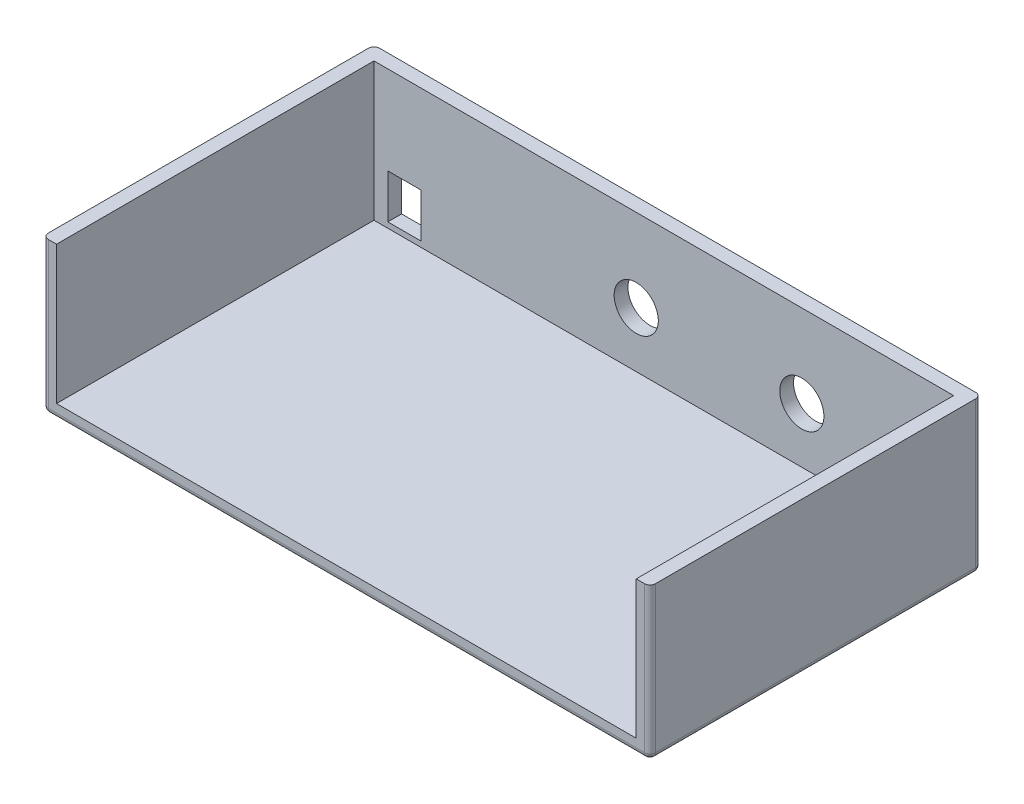
SolidWorks part; units mm, degrees
ref_plane "Alzado" through (0, 0, 0) normal (0, 0, 1) x (1, 0, 0)
ref_plane "Planta" through (0, 0, 0) normal (0, 1, 0) x (1, 0, 0)
ref_plane "Vista lateral" through (0, 0, 0) normal (1, 0, 0) x (0, 0, -1)
sketch "Croquis1" plane through (0, 0, 0) normal (0, 1, 0) x (1, 0, 0)
  line L1 (-110, -60) -> (110, -60)
  line L2 (-110, -60) -> (-110, 60)
  line L3 (-110, 60) -> (110, 60)
  line L4 (110, -60) -> (110, 60)
  line L5 (-110, -60) -> (110, 60) construction
  line L6 (-110, 60) -> (110, -60) construction
  point P0 (0, 0)
  dimension "D1" = 220
  dimension "D2" = 120
extrude "Saliente-Extruir1" add sketch "Croquis1" along normal blind 5 contours L2 L1 L4 L3
sketch "Croquis2" plane through (0, 5, 0) normal (0, 1, 0) x (1, 0, 0)
  line L0 (-110, -60) -> (110, -60) construction
  line L1 (-110, 60) -> (-105, 60)
  line L2 (-110, 60) -> (-110, -60)
  line L3 (-110, -60) -> (-105, -60)
  line L4 (-105, 55) -> (-105, -60)
  line L5 (110, 60) -> (105, 60)
  line L6 (110, 60) -> (110, -60)
  line L7 (110, -60) -> (105, -60)
  line L8 (105, 55) -> (105, -60)
  line L10 (105, 60) -> (-105, 60)
  line L12 (105, 55) -> (-105, 55)
  dimension "D1" = 5
  dimension "D2" = 5
  dimension "D3" = 5
  dimension "D5" = 115
  dimension "D6" = 5
extrude "Saliente-Extruir2" add sketch "Croquis2" along normal blind 50
sketch "Croquis3" plane through (0, 0, -60) normal (0, 0, -1) x (-1, 0, 0)
  line L1 (88, 23) -> (100, 23)
  line L2 (88, 23) -> (88, 7)
  line L3 (88, 7) -> (100, 7)
  line L4 (100, 23) -> (100, 7)
  line L5 (110, 0) -> (-110, 0) construction
  circle A0 centre (-50, 25) radius 8
  circle A1 centre (10, 25) radius 8
  circle A2 centre (-90, 25) radius 3.5
  dimension "D5" = 7
  dimension "D6" = 16
  dimension "D1" = 12
  dimension "D2" = 16
  dimension "D3" = 10
  dimension "D4" = 7
  dimension "D7" = 25
  dimension "D8" = 60
  dimension "D9" = 40
  dimension "D10" = 20
extrude "Cortar-Extruir1" cut sketch "Croquis3" against normal up to next
fillet "Redondeo1" radius 2 8 edges at (0, 0, 60) (110, 0, 0) (0, 0, -60) (-110, 0, 0) (-110, 27.5, -60) (-110, 27.5, 60) (110, 27.5, -60) (110, 27.5, 60)
